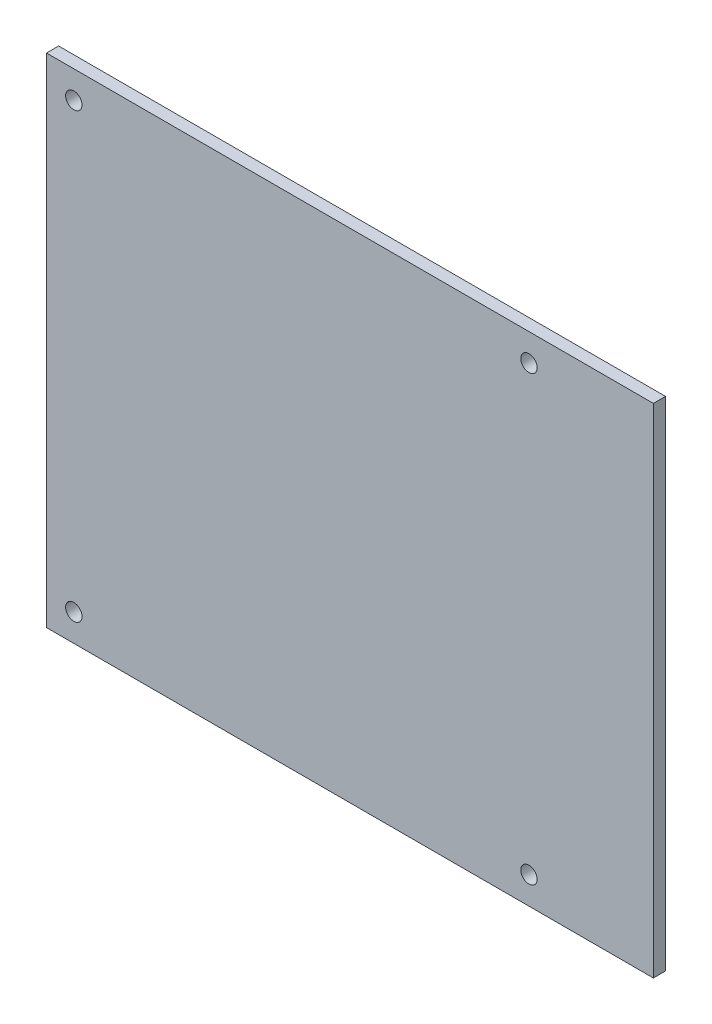
SolidWorks part; units mm, degrees
ref_plane "Plan de face" through (0, 0, 0) normal (0, 0, 1) x (1, 0, 0)
ref_plane "Plan de dessus" through (0, 0, 0) normal (0, 1, 0) x (1, 0, 0)
ref_plane "Plan de droite" through (0, 0, 0) normal (1, 0, 0) x (0, 0, -1)
sketch "Esquisse1" plane through (0, 0, 50.5) normal (0, 0, 1) x (1, 0, 0)
  line L2 (-40.6388, -13.8) -> (59.3612, -13.8)
  line L3 (-40.6388, -13.8) -> (-40.6388, -95.8)
  line L4 (-40.6388, -95.8) -> (59.3612, -95.8)
  line L5 (59.3612, -13.8) -> (59.3612, -95.8)
  circle A0 centre (-36.1388, -91.3) radius 1.35 construction
  circle A1 centre (-36.1388, -18.3) radius 1.35 construction
  circle A2 centre (38.8612, -91.3) radius 1.35 construction
  circle A3 centre (38.8612, -18.3) radius 1.35 construction
  circle A4 centre (-36.1388, -91.3) radius 1.35
  circle A5 centre (-36.1388, -18.3) radius 1.35
  circle A6 centre (38.8612, -91.3) radius 1.35
  circle A7 centre (38.8612, -18.3) radius 1.35
extrude "Boss.-Extru.1" add sketch "Esquisse1" along normal blind 2
